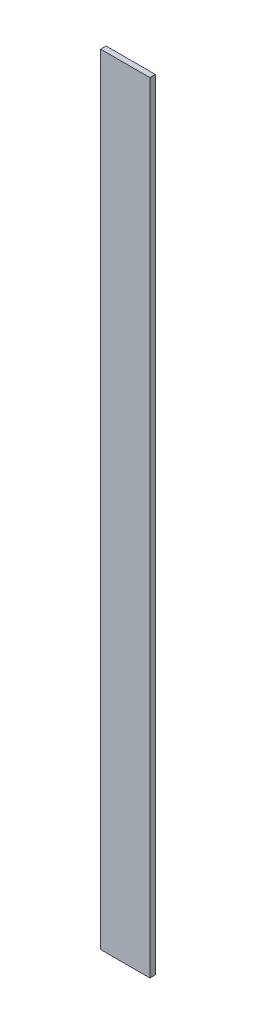
SolidWorks part; units mm, degrees
ref_plane "Front Plane" through (0, 0, 0) normal (0, 0, 1) x (1, 0, 0)
ref_plane "Top Plane" through (0, 0, 0) normal (0, 1, 0) x (1, 0, 0)
ref_plane "Right Plane" through (0, 0, 0) normal (1, 0, 0) x (0, 0, -1)
sketch "Sketch1" plane through (0, 0, 0) normal (0, 0, 1) x (1, 0, 0)
  line L1 (0, 0) -> (28.4, 0)
  line L2 (0, 0) -> (0, 450)
  line L3 (0, 450) -> (28.4, 450)
  line L4 (28.4, 0) -> (28.4, 450)
  dimension "D1" = 28.4
  dimension "D2" = 450
extrude "Boss-Extrude1" add sketch "Sketch1" along normal blind 3.175
